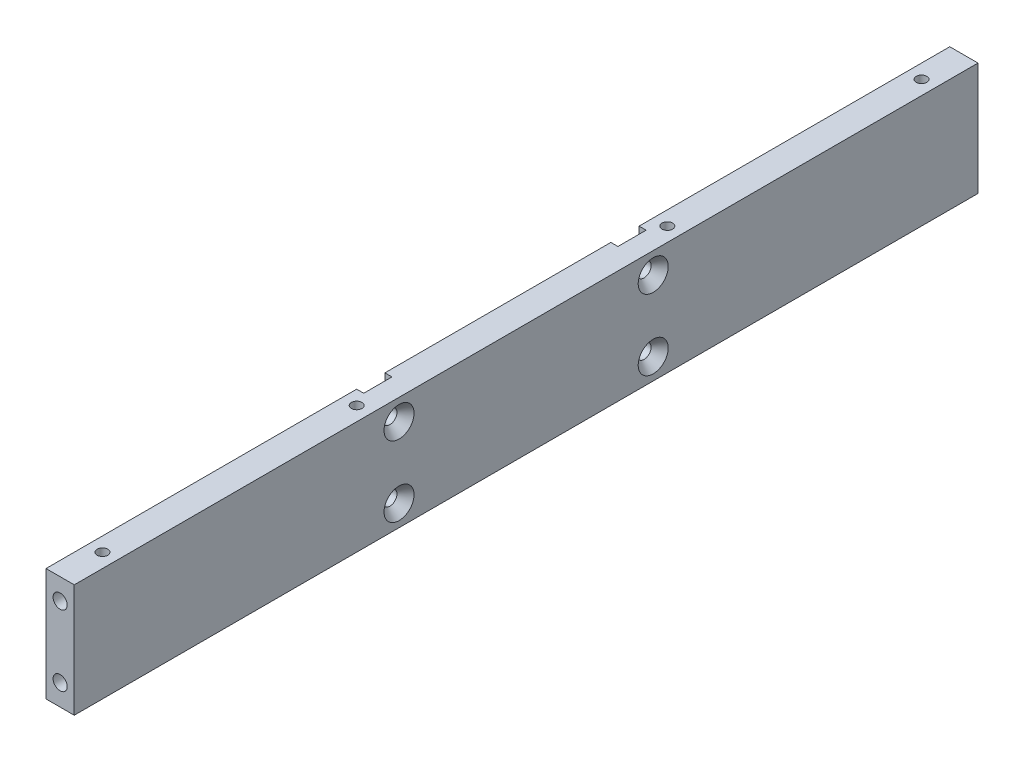
SolidWorks part; units mm, degrees
material "6061 Alloy"
ref_plane "Front Plane" through (0, 0, 0) normal (0, 0, 1) x (1, 0, 0)
ref_plane "Top Plane" through (0, 0, 0) normal (0, 1, 0) x (1, 0, 0)
ref_plane "Right Plane" through (0, 0, 0) normal (1, 0, 0) x (0, 0, -1)
sketch "Sketch1" plane through (0, 0, 0) normal (1, 0, 0) x (0, 0, -1)
  line L1 (0, 0) -> (-406.4, 0)
  line L2 (0, 0) -> (0, 50.8)
  line L3 (0, 50.8) -> (-406.4, 50.8)
  line L4 (-406.4, 0) -> (-406.4, 50.8)
  dimension "D1" = 50.8
  dimension "D2" = 406.4
extrude "Extrude1" add sketch "Sketch1" along normal blind 12.7
sketch "Sketch2" plane through (0, 0, 0) normal (-1, 0, 0) x (0, 0, 1)
  line L0 (0, 50.8) -> (406.4, 50.8) construction
  line L1 (139.7, 50.8) -> (152.4, 50.8)
  line L2 (139.7, 50.8) -> (139.7, 0)
  line L3 (139.7, 0) -> (152.4, 0)
  line L4 (152.4, 50.8) -> (152.4, 0)
  line L5 (406.4, 0) -> (0, 0) construction
  line L6 (406.4, 50.8) -> (406.4, 0) construction
  line L7 (254, 50.8) -> (266.7, 50.8)
  line L8 (254, 50.8) -> (254, 0)
  line L9 (254, 0) -> (266.7, 0)
  line L10 (266.7, 50.8) -> (266.7, 0)
  dimension "D1" = 12.7
  dimension "D2" = 12.7
  dimension "D3" = 101.6
  dimension "D4" = 139.7
extrude "Cut-Extrude1" cut sketch "Sketch2" against normal blind 3.175
sketch "Sketch3" plane through (0, 0, 0) normal (-1, 0, 0) x (0, 0, 1)
  line L0 (139.7, 0) -> (0, 0) construction
  line L1 (25.4, 41.275) -> (69.85, 41.275)
  line L2 (25.4, 41.275) -> (25.4, 9.525)
  line L3 (25.4, 9.525) -> (69.85, 9.525)
  line L4 (69.85, 41.275) -> (69.85, 9.525)
  line L5 (127, 41.275) -> (82.55, 41.275)
  line L6 (127, 41.275) -> (127, 9.525)
  line L7 (127, 9.525) -> (82.55, 9.525)
  line L8 (82.55, 41.275) -> (82.55, 9.525)
  line L9 (165.1, 41.275) -> (241.3, 41.275)
  line L10 (165.1, 41.275) -> (165.1, 9.525)
  line L11 (165.1, 9.525) -> (241.3, 9.525)
  line L12 (241.3, 41.275) -> (241.3, 9.525)
  line L13 (279.4, 41.275) -> (323.85, 41.275)
  line L14 (279.4, 41.275) -> (279.4, 9.525)
  line L15 (279.4, 9.525) -> (323.85, 9.525)
  line L16 (323.85, 41.275) -> (323.85, 9.525)
  line L17 (336.55, 41.275) -> (381, 41.275)
  line L18 (336.55, 41.275) -> (336.55, 9.525)
  line L19 (336.55, 9.525) -> (381, 9.525)
  line L20 (381, 41.275) -> (381, 9.525)
  line L21 (0, 0) -> (0, 50.8) construction
  line L22 (406.4, 50.8) -> (406.4, 0) construction
  line L23 (266.7, 0) -> (266.7, 50.8) construction
  line L24 (139.7, 50.8) -> (139.7, 0) construction
  line L25 (254, 50.8) -> (254, 0) construction
  dimension "D1" = 31.75
  dimension "D2" = 9.525
  dimension "D3" = 25.4
  dimension "D4" = 25.4
  dimension "D5" = 76.2
  dimension "D6" = 12.7
  dimension "D7" = 12.7
  dimension "D8" = 12.7
  dimension "D9" = 12.7
  dimension "D10" = 12.7
extrude "Cut-Extrude2" cut sketch "Sketch3" against normal blind 9.525
fillet "Fillet1" radius 6.35 20 edges at (4.7625, 9.525, 381) (4.7625, 9.525, 323.85) (4.7625, 9.525, 241.3) (4.7625, 9.525, 336.55) (4.7625, 9.525, 279.4) (4.7625, 9.525, 165.1) (4.7625, 41.275, 381) (4.7625, 41.275, 323.85) (4.7625, 41.275, 241.3) (4.7625, 41.275, 336.55) (4.7625, 41.275, 279.4) (4.7625, 41.275, 165.1) (4.7625, 9.525, 127) (4.7625, 9.525, 82.55) (4.7625, 41.275, 127) (4.7625, 41.275, 82.55) (4.7625, 9.525, 69.85) (4.7625, 9.525, 25.4) (4.7625, 41.275, 69.85) (4.7625, 41.275, 25.4)
sketch "Sketch4" plane through (0, 50.8, 0) normal (0, 1, 0) x (-1, 0, 0)
  line L0 (-12.7, 0) -> (-12.7, 406.4) construction
  line L1 (-12.7, 0) -> (0, 0) construction
  line L2 (-12.7, 406.4) -> (0, 406.4) construction
  circle A0 centre (-6.35, 19.05) radius 2.3813
  circle A1 centre (-6.35, 133.35) radius 2.3812
  circle A2 centre (-6.35, 273.05) radius 2.3813
  circle A3 centre (-6.35, 387.35) radius 2.3813
  dimension "D1" = 4.7625
  dimension "D2" = 6.35
  dimension "D3" = 19.05
  dimension "D4" = 19.05
  dimension "D5" = 114.3
  dimension "D6" = 114.3
extrude "Cut-Extrude3" cut sketch "Sketch4" against normal blind 15.875
ref_plane "Plane1" through (0, 25.4, 0) normal (0, 1, 0) x (-1, 0, 0)
mirror "Mirror1" about plane through (0, 25.4, 0) normal (0, 1, 0) of "Cut-Extrude3"
sketch "Sketch5" plane through (3.175, 0, 0) normal (-1, 0, 0) x (0, 0, 1)
  line L0 (139.7, 50.8) -> (139.7, 0) construction
  line L3 (152.4, 50.8) -> (139.7, 50.8) construction
  line L4 (139.7, 0) -> (152.4, 0) construction
  line L5 (254, 50.8) -> (254, 0) construction
  circle A0 centre (260.35, 41.275) radius 3.175
  circle A1 centre (260.35, 9.525) radius 3.175
  circle A2 centre (146.05, 41.275) radius 3.175
  circle A3 centre (146.05, 9.525) radius 3.175
  dimension "D1" = 6.35
  dimension "D2" = 6.35
  dimension "D3" = 9.525
  dimension "D4" = 9.525
  dimension "D5" = 6.35
extrude "Cut-Extrude4" cut sketch "Sketch5" against normal through all
sketch "Sketch6" plane through (12.7, 0, 0) normal (1, 0, 0) x (0, 0, -1)
  circle A0 centre (-260.35, 41.275) radius 6.7437
  circle A1 centre (-260.35, 9.525) radius 6.7437
  circle A2 centre (-146.05, 9.525) radius 6.7437
  circle A3 centre (-146.05, 41.275) radius 6.7437
  dimension "D1" = 13.4874
extrude "Cut-Extrude5" cut sketch "Sketch6" against normal through all draft 41
sketch "Sketch7" plane through (0, 0, 0) normal (0, 0, -1) x (-1, 0, 0)
  line L0 (-12.7, 0) -> (-12.7, 50.8) construction
  line L1 (-12.7, 50.8) -> (0, 50.8) construction
  line L2 (-12.7, 0) -> (0, 0) construction
  circle A0 centre (-6.35, 41.275) radius 3.175
  circle A1 centre (-6.35, 9.525) radius 3.175
  dimension "D1" = 6.35
  dimension "D2" = 6.35
  dimension "D3" = 9.525
  dimension "D4" = 9.525
extrude "Cut-Extrude6" cut sketch "Sketch7" against normal blind 15.875
sketch "Sketch8" plane through (0, 0, 406.4) normal (0, 0, 1) x (1, 0, 0)
  line L0 (0, 50.8) -> (0, 0) construction
  line L1 (12.7, 50.8) -> (0, 50.8) construction
  line L2 (12.7, 0) -> (0, 0) construction
  circle A0 centre (6.35, 41.275) radius 3.175
  circle A1 centre (6.35, 9.525) radius 3.175
  dimension "D1" = 6.35
  dimension "D2" = 6.35
  dimension "D3" = 9.525
  dimension "D4" = 9.525
extrude "Cut-Extrude7" cut sketch "Sketch8" against normal blind 15.875
